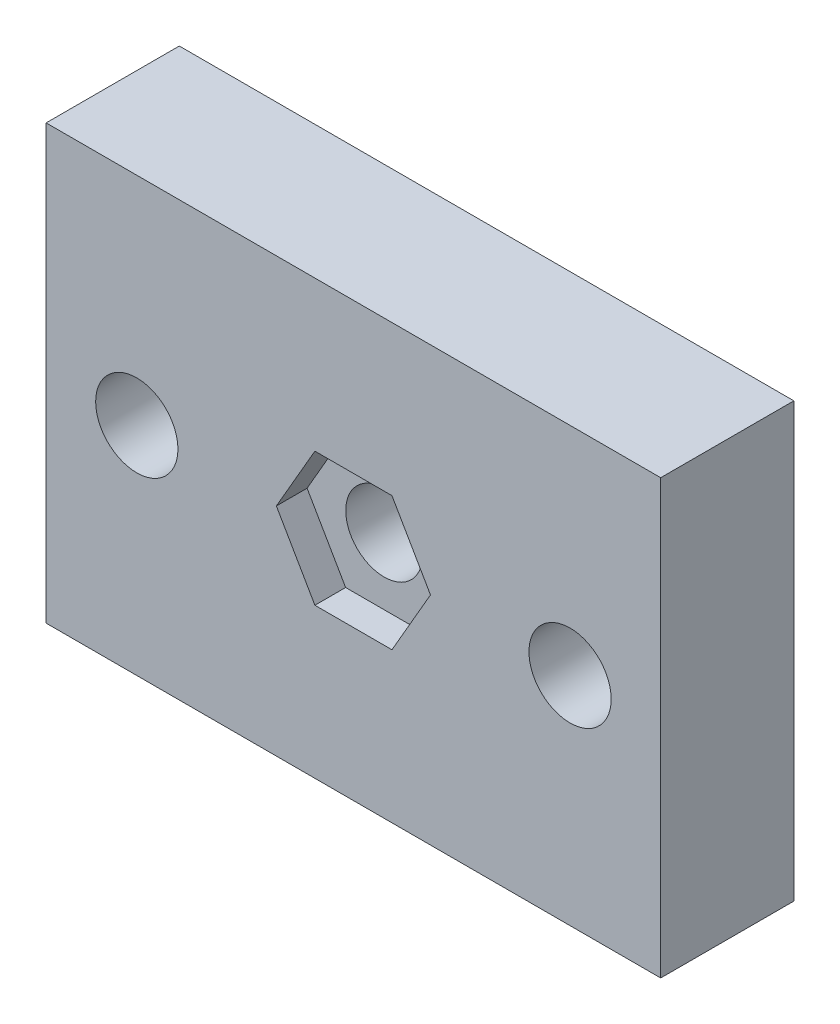
SolidWorks part; units mm, degrees
ref_plane "Front Plane" through (0, 0, 0) normal (0, 0, 1) x (1, 0, 0)
ref_plane "Top Plane" through (0, 0, 0) normal (0, 1, 0) x (1, 0, 0)
ref_plane "Right Plane" through (0, 0, 0) normal (1, 0, 0) x (0, 0, -1)
sketch "Sketch2" plane through (0, 0, 0) normal (0, 0, 1) x (1, 0, 0)
  line L1 (-28.4466, 18.9644) -> (31.5534, 18.9644)
  line L2 (-28.4466, 18.9644) -> (-28.4466, -23.3356)
  line L3 (-28.4466, -23.3356) -> (31.5534, -23.3356)
  line L4 (31.5534, 18.9644) -> (31.5534, -23.3356)
  dimension "D1" = 42.3
  dimension "D2" = 60
extrude "Boss-Extrude1" add sketch "Sketch2" along normal blind 13
sketch "Sketch3" plane through (0, 0, 13) normal (0, 0, 1) x (1, 0, 0)
  circle A0 centre (22.7034, -2.1856) radius 4.015
  circle A1 centre (-19.5966, -2.1856) radius 4.015
  dimension "D2" = 8.03
extrude "Cut-Extrude1" cut sketch "Sketch3" against normal blind 10
sketch "Sketch4" plane through (0, 0, 13) normal (0, 0, 1) x (1, 0, 0)
  line L1 (9.0763, -2.1856) -> (5.3149, 4.3294)
  line L2 (5.3149, 4.3294) -> (-2.208, 4.3294)
  line L3 (-2.208, 4.3294) -> (-5.9695, -2.1856)
  line L4 (-5.9695, -2.1856) -> (-2.208, -8.7006)
  line L5 (-2.208, -8.7006) -> (5.3149, -8.7006)
  line L6 (5.3149, -8.7006) -> (9.0763, -2.1856)
  circle A0 centre (1.5534, -2.1856) radius 6.515 construction
  dimension "D1" = 13.03
  dimension "D2" = 13.03
extrude "Cut-Extrude2" cut sketch "Sketch4" against normal blind 3
sketch "Sketch5" plane through (0, 0, 10) normal (0, 0, 1) x (1, 0, 0)
  circle A0 centre (1.5534, -2.1856) radius 3.75
  dimension "D1" = 7.5
extrude "Cut-Extrude3" cut sketch "Sketch5" against normal through all
sketch "Sketch6" plane through (0, 0, 0) normal (0, 0, -1) x (-1, 0, 0)
  line L1 (5.9695, -2.1856) -> (2.208, 4.3294)
  line L2 (2.208, 4.3294) -> (-5.3149, 4.3294)
  line L3 (-5.3149, 4.3294) -> (-9.0763, -2.1856)
  line L4 (-9.0763, -2.1856) -> (-5.3149, -8.7006)
  line L5 (-5.3149, -8.7006) -> (2.208, -8.7006)
  line L6 (2.208, -8.7006) -> (5.9695, -2.1856)
  circle A0 centre (-1.5534, -2.1856) radius 6.515 construction
  dimension "D1" = 13.03
extrude "Cut-Extrude4" cut sketch "Sketch6" against normal blind 3
